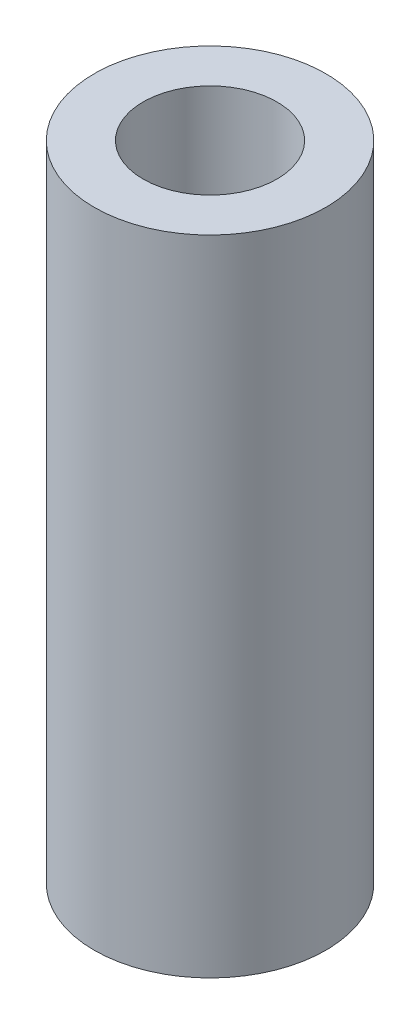
SolidWorks part; units mm, degrees
ref_plane "前视基准面" through (0, 0, 0) normal (0, 0, 1) x (1, 0, 0)
ref_plane "上视基准面" through (0, 0, 0) normal (0, 1, 0) x (1, 0, 0)
ref_plane "右视基准面" through (0, 0, 0) normal (1, 0, 0) x (0, 0, -1)
sketch "草图1" plane through (0, 0, 0) normal (0, 1, 0) x (1, 0, 0)
  circle A0 centre (0, 0) radius 4.5
  circle A1 centre (0, 0) radius 2.6
  dimension "D1" = 9
  dimension "D2" = 5.2
extrude "凸台-拉伸1" add sketch "草图1" along normal blind 25
